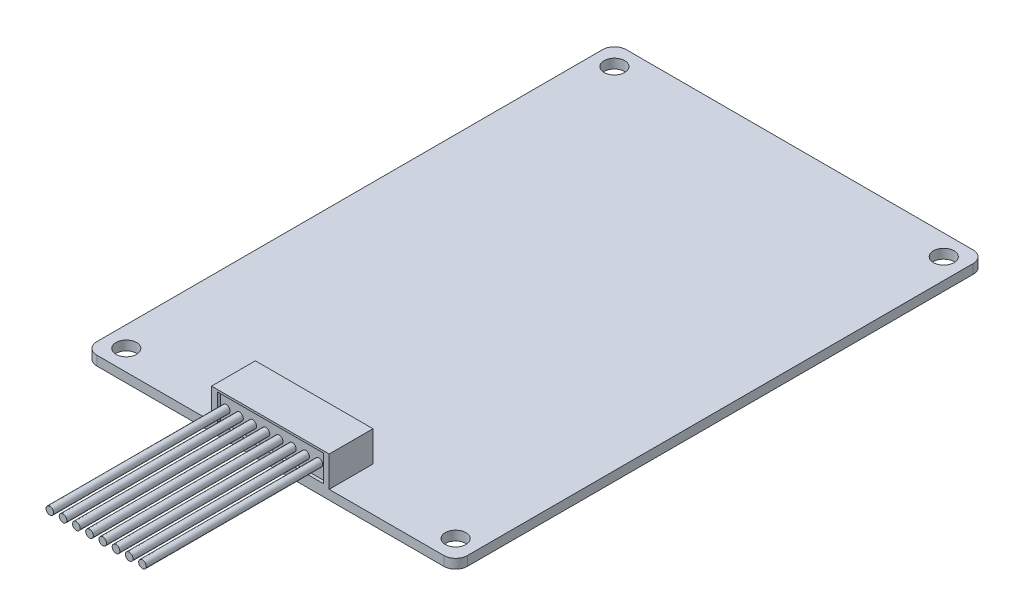
SolidWorks part; units mm, degrees
material "PVC Rigid"
ref_plane "Front Plane" through (0, 0, 0) normal (0, 0, 1) x (1, 0, 0)
ref_plane "Top Plane" through (0, 0, 0) normal (0, 1, 0) x (1, 0, 0)
ref_plane "Right Plane" through (0, 0, 0) normal (1, 0, 0) x (0, 0, -1)
sketch "Sketch1" plane through (0, 0, 0) normal (0, 1, 0) x (1, 0, 0)
  line L0 (0, 58.8443) -> (0, -69.3942) construction
  line L1 (29.5, -45) -> (-29.5, -45)
  line L2 (31.5, -43) -> (31.5, 43)
  line L3 (29.5, 45) -> (-29.5, 45)
  line L4 (-31.5, -43) -> (-31.5, 43)
  line L5 (31.5, -45) -> (-31.5, 45) construction
  line L6 (31.5, 45) -> (-31.5, -45) construction
  line L7 (-54.425, 0) -> (85.5686, 0) construction
  arc A0 (29.5, 45) -> (31.5, 43) centre (29.5, 43) cw
  arc A1 (31.5, -43) -> (29.5, -45) centre (29.5, -43) cw
  arc A2 (-31.5, -43) -> (-29.5, -45) centre (-29.5, -43) ccw
  arc A3 (-31.5, 43) -> (-29.5, 45) centre (-29.5, 43) cw
  circle A4 centre (-28, 41.5) radius 1.75
  circle A5 centre (28, 41.5) radius 1.75
  circle A6 centre (28, -41.5) radius 1.75
  circle A7 centre (-28, -41.5) radius 1.75
  point P0 (0, 0)
  point P24 (0, 0)
  dimension "D3" = 2
  dimension "D4" = 2
  dimension "D5" = 2
  dimension "D6" = 2
  dimension "D7" = 3.5
  dimension "D1" = 90
  dimension "D2" = 63
  dimension "D8" = 3.5
  dimension "D9" = 3.5
extrude "Boss-Extrude1" add sketch "Sketch1" along normal mid plane 1.6
sketch "Sketch2" plane through (0, 0.8, 0) normal (0, 1, 0) x (1, 0, 0)
  line L0 (0, 0) -> (0, -51.9955) construction
  line L1 (-29.5, -45) -> (29.5, -45) construction
  line L2 (-10, -37.55) -> (10, -37.55)
  line L3 (-10, -37.55) -> (-10, -45)
  line L4 (-10, -45) -> (10, -45)
  line L5 (10, -37.55) -> (10, -45)
  line L6 (-10, -37.55) -> (10, -45) construction
  line L7 (-10, -45) -> (10, -37.55) construction
  point P3 (0, -41.275)
  dimension "D1" = 7.45
  dimension "D2" = 20
extrude "Boss-Extrude2" add sketch "Sketch2" along normal blind 5.2
sketch "Sketch3" plane through (0, 0, 45) normal (0, 0, 1) x (1, 0, 0)
  line L0 (-10, 6) -> (10, 6) construction
  line L1 (9, 1.15) -> (-9, 1.15)
  line L2 (9, 1.15) -> (9, 5.65)
  line L3 (9, 5.65) -> (-9, 5.65)
  line L4 (-9, 1.15) -> (-9, 5.65)
  line L5 (9, 1.15) -> (-9, 5.65) construction
  line L6 (9, 5.65) -> (-9, 1.15) construction
  line L7 (-10, 6) -> (-10, 0.8) construction
  point P0 (0, 3.4)
  point P7 (0, 6)
  point P10 (-10, 3.4)
  dimension "D1" = 18
  dimension "D2" = 4.5
extrude "Cut-Extrude1" cut sketch "Sketch3" against normal blind 0.5
sketch "Sketch4" plane through (0, 0, 44.5) normal (0, 0, 1) x (1, 0, 0)
  line L0 (-9, 3.4) -> (9, 3.4) construction
  line L1 (-9, 5.65) -> (-9, 1.15) construction
  line L2 (9, 1.15) -> (9, 5.65) construction
  circle A0 centre (-8, 3.4) radius 0.65
  circle A1 centre (-5.75, 3.4) radius 0.65
  circle A2 centre (-3.5, 3.4) radius 0.65
  circle A3 centre (-1.25, 3.4) radius 0.65
  circle A4 centre (1, 3.4) radius 0.65
  circle A5 centre (3.25, 3.4) radius 0.65
  circle A6 centre (5.5, 3.4) radius 0.65
  circle A7 centre (7.75, 3.4) radius 0.65
  dimension "D1" = 1.3
  dimension "D2" = 1
  dimension "D3" = 8
extrude "Boss-Extrude3" add sketch "Sketch4" along normal blind 30
